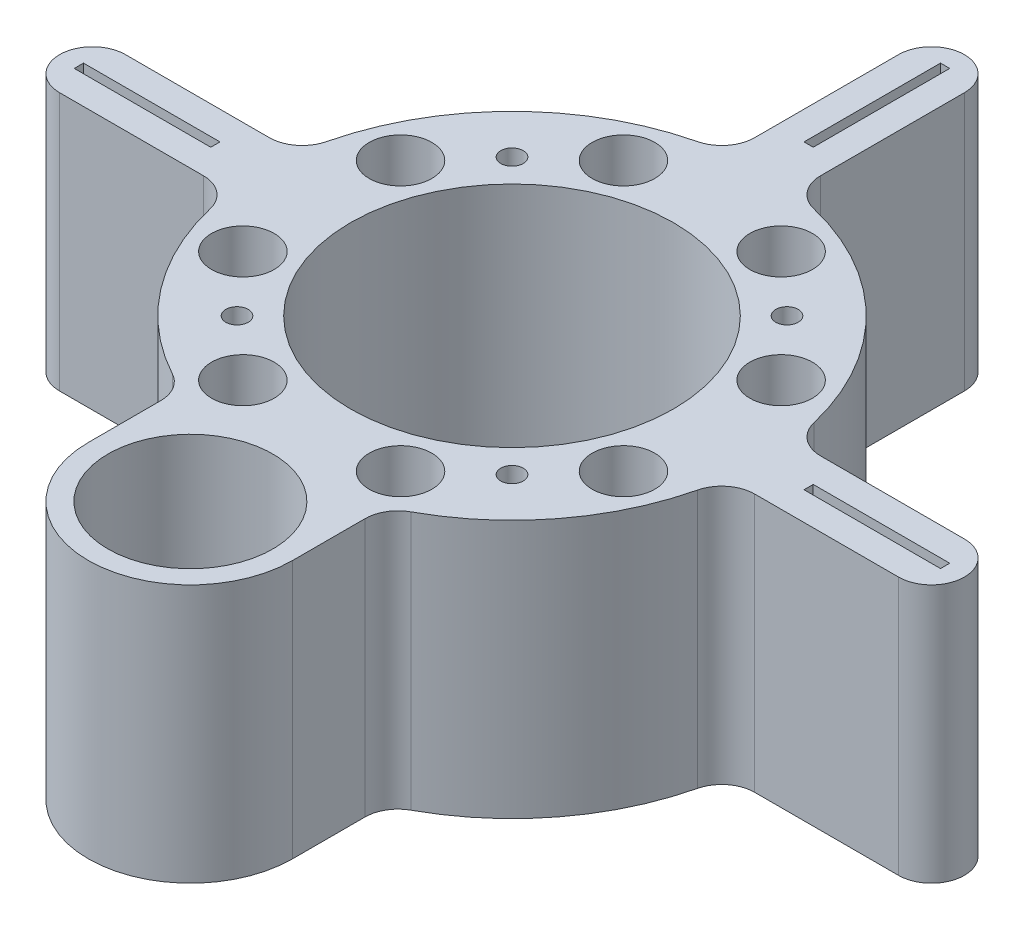
SolidWorks part; units mm, degrees
material "ABS PC"
ref_plane "Plan de face" through (0, 0, 0) normal (0, 0, 1) x (1, 0, 0)
ref_plane "Plan de dessus" through (0, 0, 0) normal (0, 1, 0) x (1, 0, 0)
ref_plane "Plan de droite" through (0, 0, 0) normal (1, 0, 0) x (0, 0, -1)
sketch "Esquisse1" plane through (0, 0, 0) normal (0, 1, 0) x (1, 0, 0)
  line L0 (0, 70.7107) -> (70.7107, 0)
  line L1 (70.7107, 0) -> (0, -70.7107)
  line L2 (0, -70.7107) -> (-70.7107, 0)
  line L3 (-70.7107, 0) -> (0, 70.7107)
  line L4 (70.7107, 0) -> (-70.7107, 0) construction
  dimension "D1" = 100
extrude "Boss.-Extru.1" add sketch "Esquisse1" along normal up to surface (39.2 mm away)
sketch "Esquisse2" plane through (0, 39.2, 0) normal (0, 1, 0) x (1, 0, 0)
  line L0 (65.7107, 0.7) -> (65.7107, -0.7)
  line L1 (-0.7, 65.7107) -> (0.7, 65.7107)
  line L2 (-0.7, 65.7107) -> (-0.7, 45)
  line L3 (-0.7, 45) -> (0.7, 45)
  line L4 (0.7, 65.7107) -> (0.7, 45)
  line L5 (65.7107, 0.7) -> (45, 0.7)
  line L6 (45, 0.7) -> (45, -0.7)
  line L7 (65.7107, -0.7) -> (45, -0.7)
  line L12 (-65.7107, -0.7) -> (-65.7107, 0.7)
  line L13 (-65.7107, -0.7) -> (-45, -0.7)
  line L14 (-45, -0.7) -> (-45, 0.7)
  line L15 (-65.7107, 0.7) -> (-45, 0.7)
  line L16 (0.7, -65.7107) -> (-0.7, -65.7107) [skipped]
  line L17 (0.7, -65.7107) -> (0.7, -45) [skipped]
  line L18 (0.7, -45) -> (-0.7, -45) [skipped]
  line L19 (-0.7, -65.7107) -> (-0.7, -45) [skipped]
  point P5 (0, 45)
  point P22 (0, 0)
  dimension "D1" = 1.4
  dimension "D2" = 45
  dimension "D3" = 5
  dimension "D4" = 4
extrude "Enlèv. mat.-Extru.1" cut sketch "Esquisse2" against normal blind 15
sketch "Esquisse3" plane through (0, 39.2, 0) normal (0, 1, 0) x (1, 0, 0)
  circle A0 centre (20.8597, 20.8597) radius 1.7
  circle A1 centre (20.8597, -20.8597) radius 1.7
  circle A2 centre (-20.8597, 20.8597) radius 1.7
  circle A3 centre (-20.8597, -20.8597) radius 1.7
  dimension "D1" = 3.4
extrude "Enlèv. mat.-Extru.2" cut sketch "Esquisse3" against normal through all
sketch "Esquisse4" plane through (0, 39.2, 0) normal (0, 1, 0) x (1, 0, 0)
  circle A0 centre (20.8597, 20.8597) radius 3.5
  circle A1 centre (20.8597, -20.8597) radius 3.5
  circle A2 centre (-20.8597, 20.8597) radius 3.5
  circle A3 centre (-20.8597, -20.8597) radius 3.5
  dimension "D1" = 7
extrude "Enlèv. mat.-Extru.3" cut sketch "Esquisse4" against normal through all from offset 5 offset against normal yes
sketch "Esquisse5" plane through (0, 39.2, 0) normal (0, 1, 0) x (1, 0, 0)
  line L0 (0, 29.5) -> (0, -29.5) construction
  line L1 (-29.5, 0) -> (29.5, 0) construction
  circle A0 centre (0, 0) radius 29.5 construction
  circle A1 centre (29.5, 0) radius 1.25
  circle A2 centre (-29.5, 0) radius 1.25
  circle A3 centre (0, -29.5) radius 1.25
  circle A4 centre (0, 29.5) radius 1.25
  point P10 (0, 0)
  point P12 (20.8597, 20.8597)
  point P13 (0, 0)
  point P15 (0, 0)
  dimension "D1" = 2.5
extrude "Enlèv. mat.-Extru.4" cut sketch "Esquisse5" against normal through all from offset 5 offset against normal yes
sketch "Esquisse6" plane through (0, 39.2, 0) normal (0, 1, 0) x (1, 0, 0)
  line L0 (0, -70.7107) -> (70.7107, 0) construction
  line L1 (-70.7107, 0) -> (0, -70.7107) construction
  circle A0 centre (0, -48.7904) radius 12.5
  dimension "D1" = 3
  dimension "D3" = 25
  dimension "D2" = 3
extrude "Enlèv. mat.-Extru.5" cut sketch "Esquisse6" against normal through all
sketch "Esquisse7" plane through (0, 39.2, 0) normal (0, 1, 0) x (1, 0, 0)
  line L0 (5, 41.821) -> (5, 63.6396)
  line L1 (70.7107, 0) -> (0, 70.7107) construction
  line L2 (0, 70.7107) -> (-70.7107, 0) construction
  line L3 (-5, 63.6396) -> (-5, 41.821)
  line L4 (41.821, -5) -> (63.6396, -5)
  line L5 (63.6396, 5) -> (41.821, 5)
  line L6 (-15.5, -37.7988) -> (-15.5, -48.7904)
  line L7 (15.5, -48.7904) -> (15.5, -37.7988)
  line L8 (-41.821, 5) -> (-63.6396, 5)
  line L9 (-63.6396, -5) -> (-41.821, -5)
  line L10 (0, -70.7107) -> (70.7107, 0) construction
  line L11 (-70.7107, 0) -> (0, -70.7107) construction
  line L12 (14.542, 35.1074) -> (9.3757, 22.635) construction
  line L13 (0.7, 45) -> (0.7, 65.7107) construction
  arc A0 (8.8372, 36.9581) -> (36.9581, 8.8372) centre (0, 0) cw
  arc A1 (5, 63.6396) -> (-5, 63.6396) centre (0, 63.6396) ccw
  arc A2 (8.8372, 36.9581) -> (5, 41.821) centre (10, 41.821) cw
  arc A3 (-5, 41.821) -> (-8.8372, 36.9581) centre (-10, 41.821) cw
  arc A4 (36.9581, -8.8372) -> (18.1163, -33.4036) centre (0, 0) cw
  arc A5 (63.6396, -5) -> (63.6396, 5) centre (63.6396, 0) ccw
  arc A6 (36.9581, -8.8372) -> (41.821, -5) centre (41.821, -10) cw
  arc A7 (41.821, 5) -> (36.9581, 8.8372) centre (41.821, 10) cw
  arc A8 (-18.1163, -33.4036) -> (-36.9581, -8.8372) centre (0, 0) cw
  arc A9 (-15.5, -48.7904) -> (15.5, -48.7904) centre (0, -48.7904) ccw
  arc A10 (-18.1163, -33.4036) -> (-15.5, -37.7988) centre (-20.5, -37.7988) cw
  arc A11 (15.5, -37.7988) -> (18.1163, -33.4036) centre (20.5, -37.7988) cw
  arc A12 (-36.9581, 8.8372) -> (-8.8372, 36.9581) centre (0, 0) cw
  arc A13 (-63.6396, 5) -> (-63.6396, -5) centre (-63.6396, 0) ccw
  arc A14 (-36.9581, 8.8372) -> (-41.821, 5) centre (-41.821, 10) cw
  arc A15 (-41.821, -5) -> (-36.9581, -8.8372) centre (-41.821, -10) cw
  circle A16 centre (0, -48.7904) radius 12.5 construction
  circle A17 centre (0, 0) radius 24.5
  circle A18 centre (11.9589, 28.8712) radius 4.75
  circle A19 centre (28.8712, 11.9589) radius 4.75
  circle A20 centre (28.8712, -11.9589) radius 4.75
  circle A21 centre (11.9589, -28.8712) radius 4.75
  circle A22 centre (-11.9589, -28.8712) radius 4.75
  circle A23 centre (-28.8712, -11.9589) radius 4.75
  circle A24 centre (-28.8712, 11.9589) radius 4.75
  circle A25 centre (-11.9589, 28.8712) radius 4.75
  point P49 (0, 0)
  point P72 (0, 0)
  dimension "D1" = 49
  dimension "D2" = 38
  dimension "D3" = 5
  dimension "D4" = 9.5
  dimension "D6" = 2
  dimension "D5" = 22.5
  dimension "D7" = 8
extrude "Enlèv. mat.-Extru.6" cut sketch "Esquisse7" against normal through all flip side to cut
